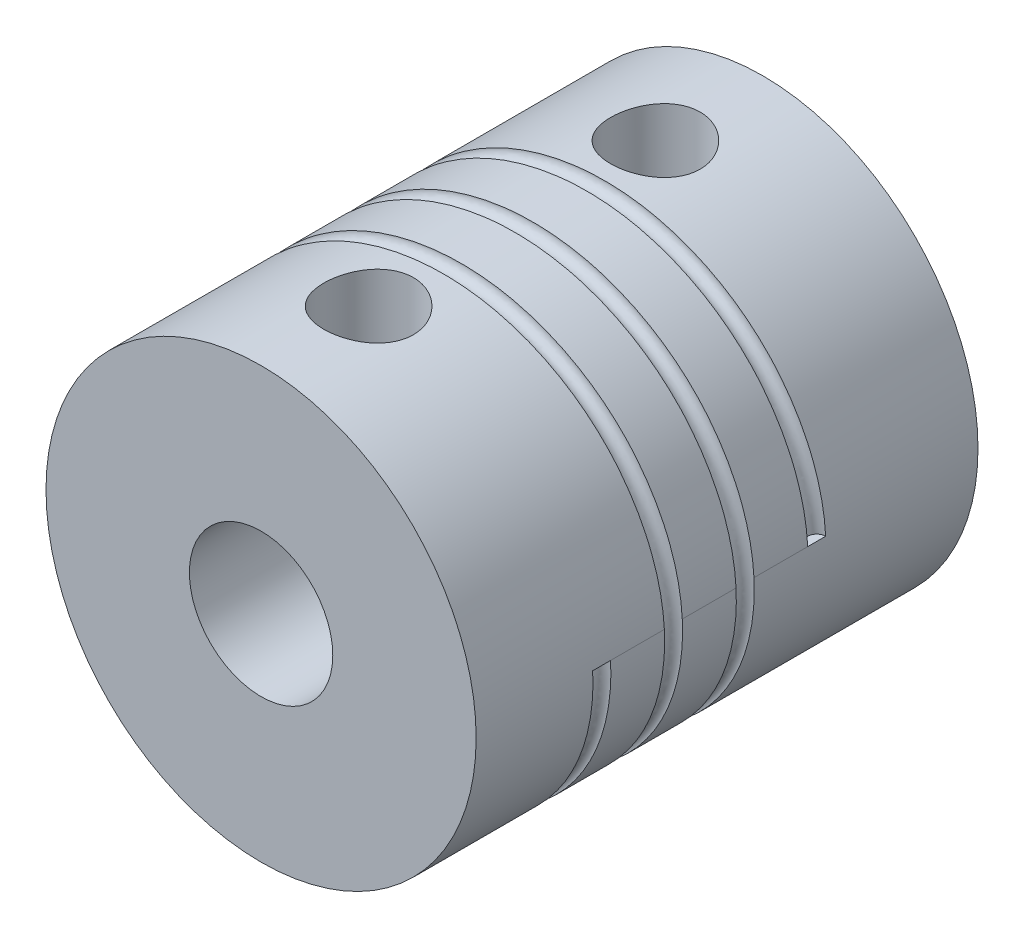
SolidWorks part; units mm, degrees
material "6061 合金"
ref_plane "前视基准面" through (0, 0, 0) normal (0, 0, 1) x (1, 0, 0)
ref_plane "上视基准面" through (0, 0, 0) normal (0, 1, 0) x (1, 0, 0)
ref_plane "右视基准面" through (0, 0, 0) normal (1, 0, 0) x (0, 0, -1)
sketch "草图1" plane through (0, 0, 0) normal (0, 0, 1) x (1, 0, 0)
  circle A0 centre (0, 0) radius 1.5
  circle A1 centre (0, 0) radius 6
  dimension "D1" = 3
  dimension "D2" = 12
extrude "凸台-拉伸1" add sketch "草图1" along normal blind 14
sketch "草图2" plane through (0, 0, 0) normal (0, 1, 0) x (1, 0, 0)
  line L0 (0, -14) -> (0, -11) construction
  line L1 (-6, -14) -> (6, -14) construction
  line L2 (0, -11) -> (0, -3) construction
  circle A0 centre (0, -3) radius 1.25
  circle A1 centre (0, -11) radius 1.25
  dimension "D3" = 2.5
  dimension "D4" = 2.5
  dimension "D1" = 3
  dimension "D2" = 8
extrude "切除-拉伸1" cut sketch "草图2" along normal blind 7
ref_plane "基准面1" through (0, 0, 4.5) normal (0, 0, -1) x (-1, 0, 0)
sketch "草图3" plane through (0, 0, 4.5) normal (0, 0, -1) x (-1, 0, 0)
  circle A0 centre (0, 0) radius 6
curve "螺旋线/涡状线1" pitch 2 height 6 turns 3
sketch "草图4" plane through (0, 0, 0) normal (0, 1, 0) x (1, 0, 0)
  line L0 (6, -14) -> (6, 0) construction
  circle A0 centre (6, -10.5) radius 0.25
  spline S0 degree 3 poles (6, -4.5) (6, -4.5414) (5.6876, -4.6251) (4.3531, -4.75) (2.3559, -4.875) (0, -5) (-2.3559, -5.125) (-4.3531, -5.25) (-5.6876, -5.375) (-6.1562, -5.5) (-5.6876, -5.625) (-4.3531, -5.75) (-2.3559, -5.875) (0, -6) (2.3559, -6.125) (4.3531, -6.25) (5.6876, -6.375) (6.1562, -6.5) (5.6876, -6.625) (4.3531, -6.75) (2.3559, -6.875) (0, -7) (-2.3559, -7.125) (-4.3531, -7.25) (-5.6876, -7.375) (-6.1562, -7.5) (-5.6876, -7.625) (-4.3531, -7.75) (-2.3559, -7.875) (0, -8) (2.3559, -8.125) (4.3531, -8.25) (5.6876, -8.375) (6.1562, -8.5) (5.6876, -8.625) (4.3531, -8.75) (2.3559, -8.875) (0, -9) (-2.3559, -9.125) (-4.3531, -9.25) (-5.6876, -9.375) (-6.1562, -9.5) (-5.6876, -9.625) (-4.3531, -9.75) (-2.3559, -9.875) (0, -10) (2.3559, -10.125) (4.3531, -10.25) (5.6876, -10.3749) (6, -10.4586) (6, -10.5) knots 0 0 0 0 0.020833 0.041667 0.0625 0.083333 0.104167 0.125 0.145833 0.166667 0.1875 0.208333 0.229167 0.25 0.270833 0.291667 0.3125 0.333333 0.354167 0.375 0.395833 0.416667 0.4375 0.458333 0.479167 0.5 0.520833 0.541667 0.5625 0.583333 0.604167 0.625 0.645833 0.666667 0.6875 0.708333 0.729167 0.75 0.770833 0.791667 0.8125 0.833333 0.854167 0.875 0.895833 0.916667 0.9375 0.958333 0.979167 1 1 1 1 construction
  dimension "D1" = 0.5
sweep "切除-扫描1" cut profiles "草图4" path "螺旋线/涡状线1"
sketch "草图5" plane through (0, 0, 14) normal (0, 0, 1) x (1, 0, 0)
  circle A0 centre (0, 0) radius 2
  dimension "D1" = 4
extrude "切除-拉伸2" cut sketch "草图5" against normal blind 9
